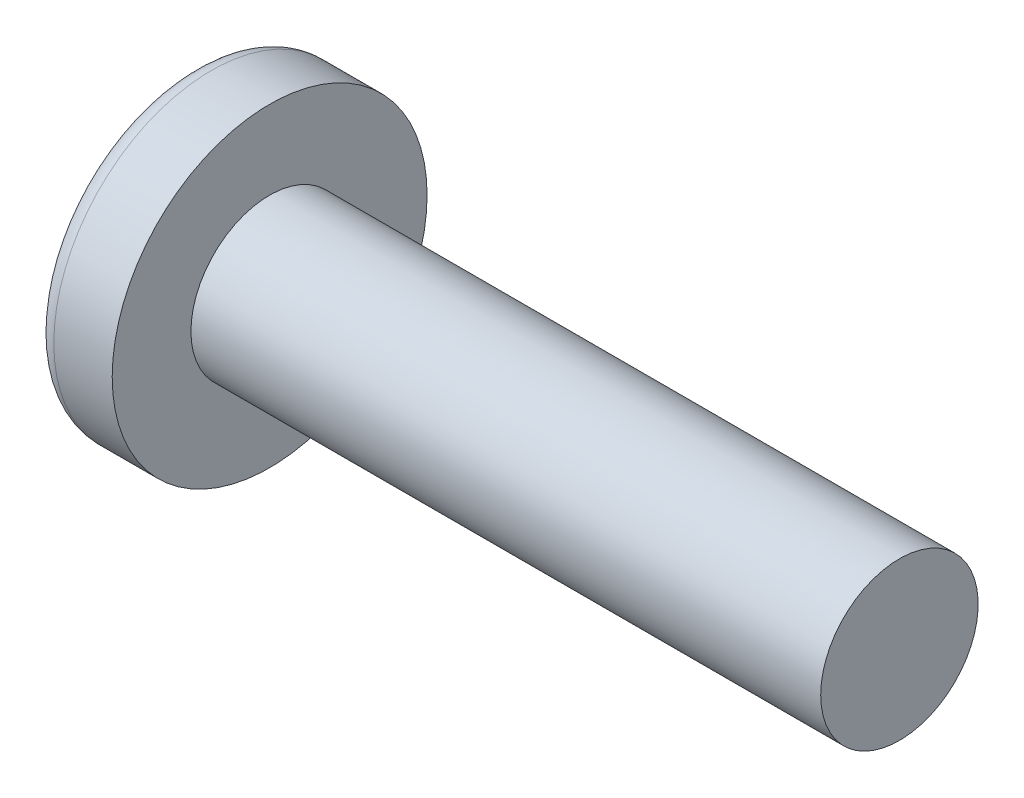
SolidWorks part; units mm, degrees
ref_plane "Plane1" through (0, 0, 0) normal (0, 0, 1) x (1, 0, 0)
ref_plane "Plane2" through (0, 0, 0) normal (0, 1, 0) x (1, 0, 0)
ref_plane "Plane3" through (0, 0, 0) normal (1, 0, 0) x (0, 0, -1)
sketch "BodySke" plane through (0, 0, 0) normal (0, 0, 1) x (1, 0, 0)
  line L0 (3.1, 2) -> (3.1, 4)
  line L1 (3.8, 6.35) -> (3.8, -3.175) construction
  line L2 (-25.4, 0) -> (127, 0) construction
  line L3 (19.1, 0) -> (0, 0)
  line L4 (3.1, 2) -> (19.1, 2)
  line L5 (19.1, 2) -> (19.1, 0)
  line L6 (1.6164, 4) -> (3.1, 4)
  line L7 (3.1, -2) -> (19.1, -2) construction
  line L8 (3.1, 6.35) -> (3.1, -3.175) construction
  arc A0 (1.227, 3.8007) -> (0, 0) centre (6.5, 0) ccw
  arc A2 (1.227, 3.8007) -> (1.6164, 4) centre (1.6164, 3.52) cw
  dimension "Head_crown_rad" = 6.5
  dimension "Head_fillet_rad" = 0.48
  dimension "Diameter" = 4
  dimension "Length" = 16
  dimension "Head_ht" = 3.1
  dimension "Head_dia" = 8
  dimension "Advance" = 0.7
  dimension "Thread_nom" = 16
revolve "Base-Revolve" add sketch "BodySke" angle 360 about L2
cosmetic thread "ThreadCosmetic" [suppressed] parameters "Thread_length"=15.3, "Thread_minor"=3.22
sketch "Sketch3" plane through (0, 0, 0) normal (1, 0, 0) x (0, 0, -1)
  line L0 (0.465, -2.2) -> (-0.465, -2.2)
  line L1 (0.465, -2.2) -> (0.465, 2.2)
  line L2 (-0.465, 2.2) -> (0.465, 2.2)
  line L3 (-0.465, 2.2) -> (-0.465, -2.2)
  dimension "Cross_dia" = 4.4
  dimension "D1" = 2.2
  dimension "Cross_width" = 0.93
  dimension "D2" = 0.465
ref_plane "Plane4" through (2.45, 0, 0) normal (1, 0, 0) x (0, 0, -1)
sketch "Sketch4" plane through (2.45, 0, 0) normal (1, 0, 0) x (0, 0, -1)
  line L0 (0.2325, -0.2325) -> (-0.2325, -0.2325)
  line L1 (0.2325, -0.2325) -> (0.2325, 0.2325)
  line L2 (-0.2325, 0.2325) -> (0.2325, 0.2325)
  line L3 (-0.2325, 0.2325) -> (-0.2325, -0.2325)
  dimension "D2" = 0.465
  dimension "D1" = 0.465
  dimension "D3" = 0.2325
  dimension "D4" = 0.2325
loft "Cut-Loft1" cut profiles "Sketch3", "Sketch4"
pattern_circular "CirPattern1" count 2 every 90 about axis through (0, 0, 0) along (1, 0, 0) of "Cut-Loft1"
sketch "ThdSchSke" plane through (0, 0, 0) normal (0, 0, 1) x (1, 0, 0)
  line L0 (3.8, -1.61) -> (3.5269, -2)
  line L1 (3.8, -1.61) -> (4.0731, -2)
  line L2 (4.0731, -2) -> (4.0731, -2.5)
  line L3 (-3.175, 0) -> (5.1513, 0) construction
  line L5 (4.0731, -2.5) -> (3.5269, -2.5)
  line L6 (3.5269, -2.5) -> (3.5269, -2)
  dimension "Diameter" = 4
  dimension "SideAngle" = 55
  dimension "VeeAngle" = 70
  dimension "Thread_minor" = 3.22
  dimension "Overcut" = 5
  dimension "Start" = 3.8
revolve "ThreadSchematic" [suppressed] cut sketch "ThdSchSke" angle 360 about L3
pattern_linear "ThdSchPat" [suppressed]
equation "\"D1@Sketch3\" = \"Cross_dia@Sketch3\" / 2"
equation "\"D2@Sketch3\" = \"Cross_width@Sketch3\" / 2"
equation "\"D1@Sketch4\" = \"Cross_width@Sketch3\" *.5"
equation "\"D2@Sketch4\" = \"D1@Sketch4\""
equation "\"D3@Sketch4\" = \"D1@Sketch4\" / 2"
equation "\"D4@Sketch4\" = \"D2@Sketch4\" / 2"
equation "\"Thread_length@ThreadCosmetic\" = ((sgn( (\"Length@BodySke\" - \"Advance@BodySke\" ) - \"Thread_nom@BodySke\" )-1)*( (\"Length@BodySke\" - \"Advance@BodySke\" ) - \"Thread_nom@BodySke\" ))/-2+ \"Thread_nom@BodySke\""
equation "\"Thread_minor@ThdSchSke\" = \"Thread_minor@ThreadCosmetic\""
equation "\"Diameter@ThdSchSke\" = \"Diameter@BodySke\""
equation "\"Overcut@ThdSchSke\" = \"Diameter@BodySke\" * 1.25"
equation "\"Start@ThdSchSke\" = \"Head_ht@BodySke\" + \"Length@BodySke\" - \"Thread_length@ThreadCosmetic\"  '---Non-countersunk---"
equation "\"Num_threads@ThdSchPat\" = int( \"Thread_length@ThreadCosmetic\" / \"Advance@BodySke\" + 0.999 )  + 1"
equation "\"Advance@ThdSchPat\" = \"Thread_length@ThreadCosmetic\" /  (\"Num_threads@ThdSchPat\" - 1) 'relax it"
